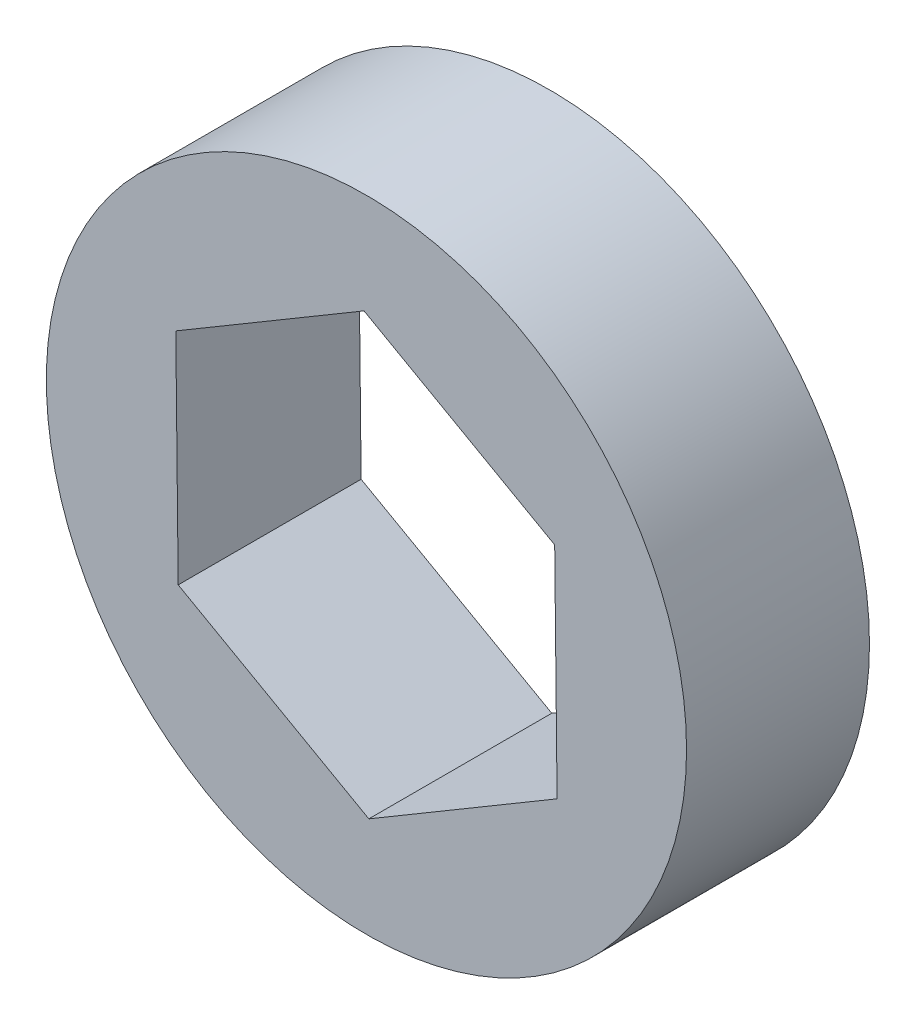
SolidWorks part; units mm, degrees
ref_plane "Front Plane" through (0, 0, 0) normal (0, 0, 1) x (1, 0, 0)
ref_plane "Top Plane" through (0, 0, 0) normal (0, 1, 0) x (1, 0, 0)
ref_plane "Right Plane" through (0, 0, 0) normal (1, 0, 0) x (0, 0, -1)
sketch "Sketch1" plane through (0, 0, 0) normal (0, 0, 1) x (1, 0, 0)
  line L1 (7.2954, -4.1061) -> (7.2037, 4.265)
  line L2 (7.2037, 4.265) -> (-0.0917, 8.3711)
  line L3 (-0.0917, 8.3711) -> (-7.2954, 4.1061)
  line L4 (-7.2954, 4.1061) -> (-7.2037, -4.265)
  line L5 (-7.2037, -4.265) -> (0.0917, -8.3711)
  line L6 (0.0917, -8.3711) -> (7.2954, -4.1061)
  circle A1 centre (0, 0) radius 12.25
  circle A2 centre (0, 0) radius 7.25 construction
  dimension "D1" = 14.5
  dimension "D2" = 24.5
extrude "Boss-Extrude1" add sketch "Sketch1" along normal blind 7
